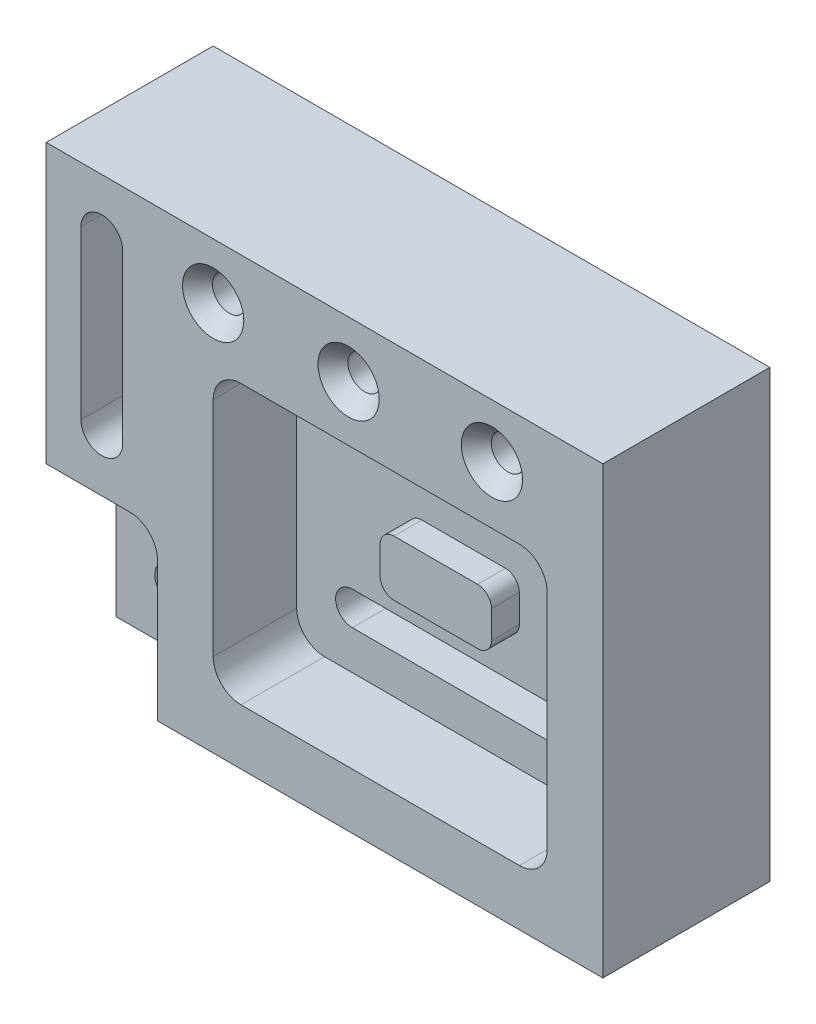
SolidWorks part; units mm, degrees
ref_plane "Plane1" through (0, 0, 0) normal (0, 0, 1) x (1, 0, 0)
ref_plane "Plane2" through (0, 0, 0) normal (0, 1, 0) x (1, 0, 0)
ref_plane "Plane3" through (0, 0, 0) normal (1, 0, 0) x (0, 0, -1)
sketch "Sketch1" plane through (0, 0, 0) normal (0, 0, 1) x (1, 0, 0)
  line L0 (-100, 80) -> (100, 80)
  line L1 (-100, 80) -> (-100, -80)
  line L2 (100, -80) -> (-100, -80)
  line L3 (100, -80) -> (100, 80)
extrude "Base-Extrude" add sketch "Sketch1" against normal blind 60
sketch "Sketch2" plane through (0, 0, 0) normal (0, 0, 1) x (1, 0, 0)
  line L0 (-30, 40) -> (70, 40)
  line L1 (-40, 30) -> (-40, -50)
  line L2 (70, -60) -> (-30, -60)
  line L3 (80, -50) -> (80, 30)
  arc A0 (80, 30) -> (70, 40) centre (70, 30) ccw
  arc A1 (80, -50) -> (70, -60) centre (70, -50) cw
  arc A2 (-30, -60) -> (-40, -50) centre (-30, -50) cw
  arc A3 (-40, 30) -> (-30, 40) centre (-30, 30) cw
  dimension "D1" = 10
extrude "Cut-Extrude1" cut sketch "Sketch2" against normal blind 30
sketch "Sketch3" plane through (0, 0, 0) normal (0, 0, 1) x (1, 0, 0)
  line L0 (-120, -20) -> (-70, -20)
  line L1 (-120, -20) -> (-120, -100)
  line L2 (-60, -100) -> (-120, -100)
  line L3 (-60, -100) -> (-60, -30)
  arc A0 (-60, -30) -> (-70, -20) centre (-70, -30) ccw
  dimension "D1" = 10
extrude "Cut-Extrude2" cut sketch "Sketch3" against normal blind 25
hole_wizard "Hole1" positions "Sketch8" profile "Sketch7" legacy
sketch "Sketch8" plane through (0, 0, 0) normal (0, 0, 1) x (1, 0, 0)
  point P0 (-40, 60)
sketch "Sketch7" plane through (-40, 60, 0) normal (1, 0, 0) x (0, -1, 0)
  line L0 (0, 0) -> (0, 60)
  line L1 (0, 60) -> (6, 60)
  line L2 (6, 60) -> (6, 5.7518)
  line L3 (6, 5.7518) -> (11, 0)
  line L4 (11, 0) -> (0, 0)
  line L5 (0, -6.4453) -> (0, 115.525) construction
  line L6 (-6, 5.7518) -> (-11, 0) construction
  dimension "Diameter" = 12
  dimension "Depth" = 60
  dimension "C-Sink Angle" = 82
  dimension "C-Sink Diameter" = 22
hole_wizard "Hole4" positions "Sketch17" profile "Sketch18" legacy
sketch "Sketch17" plane through (41.9973, -0.1277, 0) normal (0, 0, 1) x (1, 0, 0)
  point P0 (-33.3333, 60)
sketch "Sketch18" plane through (8.6639, 59.8723, 0) normal (1, 0, 0) x (0, -1, 0)
  line L0 (0, 0) -> (0, 60)
  line L1 (0, 60) -> (6, 60)
  line L2 (6, 60) -> (6, 5.7518)
  line L3 (6, 5.7518) -> (11, 0)
  line L4 (11, 0) -> (0, 0)
  line L5 (0, -6.4453) -> (0, 115.525) construction
  line L6 (-6, 5.7518) -> (-11, 0) construction
  dimension "Diameter" = 12
  dimension "Depth" = 60
  dimension "C-Sink Angle" = 82
  dimension "C-Sink Diameter" = 22
hole_wizard "Hole5" positions "Sketch19" profile "Sketch20" legacy
sketch "Sketch19" plane through (100.1484, 0.6571, 0) normal (0, 0, 1) x (1, 0, 0)
  point P0 (-40, 60)
sketch "Sketch20" plane through (60.1484, 60.6571, 0) normal (1, 0, 0) x (0, -1, 0)
  line L0 (0, 0) -> (0, 60)
  line L1 (0, 60) -> (6, 60)
  line L2 (6, 60) -> (6, 5.7518)
  line L3 (6, 5.7518) -> (11, 0)
  line L4 (11, 0) -> (0, 0)
  line L5 (0, -6.4453) -> (0, 115.525) construction
  line L6 (-6, 5.7518) -> (-11, 0) construction
  dimension "Diameter" = 12
  dimension "Depth" = 60
  dimension "C-Sink Angle" = 82
  dimension "C-Sink Diameter" = 22
sketch "Sketch21" plane through (0, 0, -25) normal (0, 0, 1) x (1, 0, 0)
  circle A0 centre (-80, -33.3333) radius 6
  circle A1 centre (-80, -60) radius 6
  dimension "D1" = 12
  dimension "D2" = 12
extrude "Cut-Extrude4" cut sketch "Sketch21" against normal through all
sketch "Sketch22" plane through (0, 0, 0) normal (0, 0, 1) x (1, 0, 0)
  line L0 (-72.5, 60) -> (-72.5, 0)
  line L1 (-87.5, 60) -> (-87.5, 0)
  arc A0 (-87.5, 0) -> (-72.5, 0) centre (-80, 0) ccw
  arc A1 (-72.5, 60) -> (-87.5, 60) centre (-80, 60) ccw
  dimension "D1" = 15
  dimension "D2" = 15
extrude "Cut-Extrude5" cut sketch "Sketch22" against normal blind 25
sketch "Sketch23" plane through (0, 0, -30) normal (0, 0, 1) x (1, 0, 0)
  line L0 (-20, 26) -> (60.1484, 26)
  line L1 (-20, 14) -> (60.1484, 14)
  line L2 (-20, -34) -> (60.1484, -34)
  line L3 (-20, -46) -> (60.1484, -46)
  arc A0 (-20, 26) -> (-20, 14) centre (-20, 20) ccw
  arc A1 (60.1484, 14) -> (60.1484, 26) centre (60.1484, 20) ccw
  arc A2 (-20, -34) -> (-20, -46) centre (-20, -40) ccw
  arc A3 (60.1484, -46) -> (60.1484, -34) centre (60.1484, -40) ccw
  dimension "D1" = 12
  dimension "D2" = 12
  dimension "D3" = 12
  dimension "D4" = 12
extrude "Cut-Extrude6" cut sketch "Sketch23" against normal through all
sketch "Sketch24" plane through (0, 0, -30) normal (0, 0, 1) x (1, 0, 0)
  line L0 (5, 0) -> (35, 0)
  line L1 (0, -5) -> (0, -15)
  line L2 (35, -20) -> (5, -20)
  line L3 (40, -15) -> (40, -5)
  arc A0 (40, -5) -> (35, 0) centre (35, -5) ccw
  arc A1 (40, -15) -> (35, -20) centre (35, -15) cw
  arc A2 (5, -20) -> (0, -15) centre (5, -15) cw
  arc A3 (0, -5) -> (5, 0) centre (5, -5) cw
  point P13 (0, 0)
  dimension "D1" = 5
extrude "Boss-Extrude1" add sketch "Sketch24" along normal blind 10
